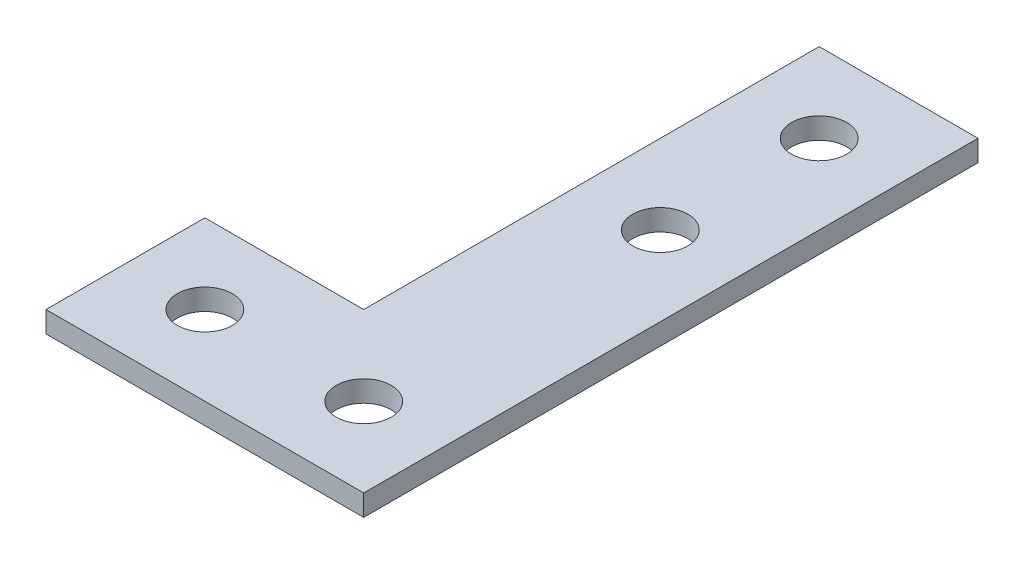
SolidWorks part; units mm, degrees
ref_plane "前视基准面" through (0, 0, 0) normal (0, 0, 1) x (1, 0, 0)
ref_plane "上视基准面" through (0, 0, 0) normal (0, 1, 0) x (1, 0, 0)
ref_plane "右视基准面" through (0, 0, 0) normal (1, 0, 0) x (0, 0, -1)
other "Configuration Table"
sketch "草图1" plane through (0, 0, 0) normal (0, 1, 0) x (1, 0, 0)
  line L0 (0, 0) -> (0, 20.5) construction
  line L1 (0, 0) -> (7.5, 0)
  line L2 (7.5, 0) -> (7.5, 13)
  line L3 (7.5, 13) -> (0, 13) construction
  line L4 (7.5, 13) -> (7.5, 28)
  line L5 (7.5, 28) -> (-7.5, 28) construction
  line L6 (7.5, 0) -> (7.5, -15)
  line L7 (7.5, -15) -> (-22.5, -15)
  line L8 (-7.5, 13) -> (-7.5, 28)
  line L9 (-7.5, 0) -> (-7.5, 13)
  line L10 (-7.5, 0) -> (-22.5, 0)
  line L11 (-22.5, 0) -> (-22.5, -15) construction
  line L12 (-15, 0) -> (-15, -19.0647) construction
  line L13 (-22.5, -7.5) -> (-11.1899, -7.5) construction
  line L14 (-11.5111, 20.5) -> (13.1629, 20.5) construction
  line L15 (-7.5, 0) -> (-7.5, -9.2649) construction
  line L18 (-7.5, 28) -> (-7.5, 43)
  line L19 (-7.5, 43) -> (7.5, 43)
  line L20 (7.5, 43) -> (7.5, 28)
  line L21 (-22.5, 0) -> (-22.5, -15)
  circle A0 centre (-15, -7.5) radius 2.6
  circle A1 centre (0, 20.5) radius 2.6
  circle A3 centre (0, 35.5) radius 2.6
  circle A4 centre (0, -7.5) radius 2.6
  point P11 (0, 28)
  dimension "D8" = 5.2
  dimension "D1" = 13
  dimension "D2" = 15
  dimension "D3" = 15
  dimension "D4" = 15
  dimension "D5" = 15
  dimension "D7" = 7.5
  dimension "D10" = 15
extrude "凸台-拉伸1" add sketch "草图1" along normal blind 2
